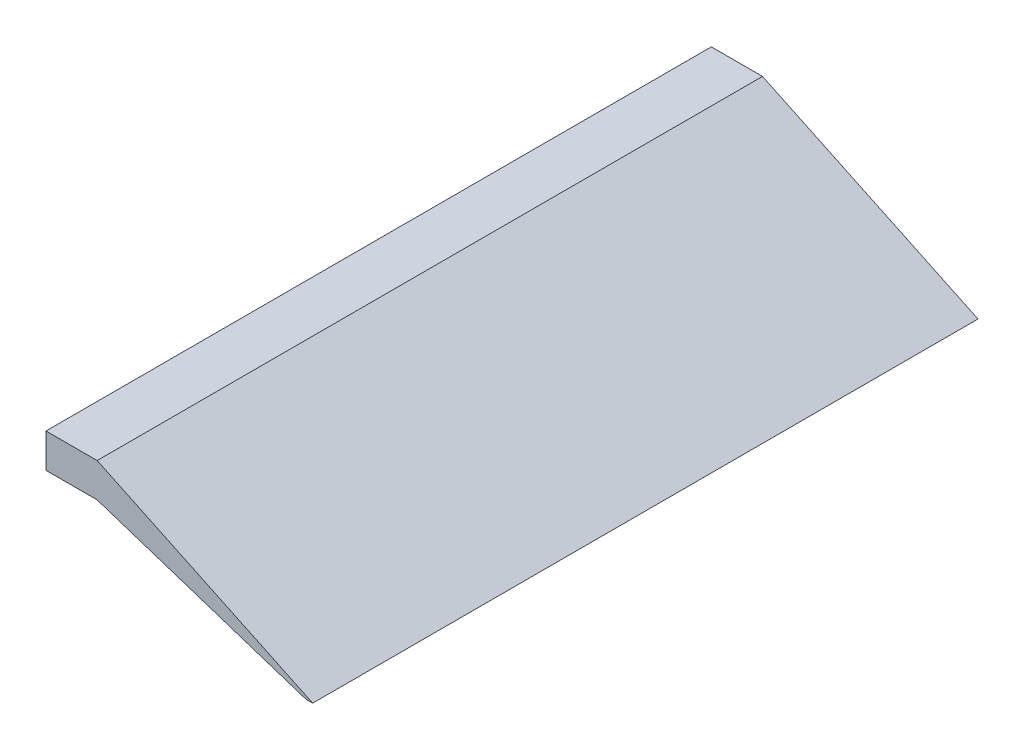
SolidWorks part; units mm, degrees
ref_plane "Front Plane" through (0, 0, 0) normal (0, 0, 1) x (1, 0, 0)
ref_plane "Top Plane" through (0, 0, 0) normal (0, 1, 0) x (1, 0, 0)
ref_plane "Right Plane" through (0, 0, 0) normal (1, 0, 0) x (0, 0, -1)
sketch "Sketch3" plane through (0, 0, 0) normal (1, 0, 0) x (0, 0, -1)
  line L0 (0, 6.3151) -> (0, -6.3151) construction
  line L1 (-97.5, 10) -> (97.5, 10)
  line L2 (-97.5, 10) -> (-97.5, 0)
  line L3 (-97.5, 0) -> (97.5, 0)
  line L4 (97.5, 10) -> (97.5, 0)
  line L5 (-97.5, 10) -> (97.5, 0) construction
  line L6 (-97.5, 0) -> (97.5, 10) construction
  point P0 (0, 5)
  point P5 (0, 0)
  dimension "D1" = 0
  dimension "D2" = 10
  dimension "D3" = 195
extrude "Boss-Extrude1" add sketch "Sketch3" against normal blind 15
sketch "Sketch4" plane through (0, 0, 0) normal (0, 0, 1) x (1, 0, 0)
  line L0 (61.1636, -20) -> (63.1636, -20)
  line L2 (55, 0) -> (-55, 0) construction
  line L3 (0, 0) -> (61.1636, -20)
  line L4 (0, 10) -> (63.1636, -20)
  line L5 (0, 0) -> (0, 10)
  dimension "D1" = 20
  dimension "D2" = 2
extrude "Boss-Extrude2" add sketch "Sketch4" along normal mid plane 195 contours L4 L0 L3 L5
